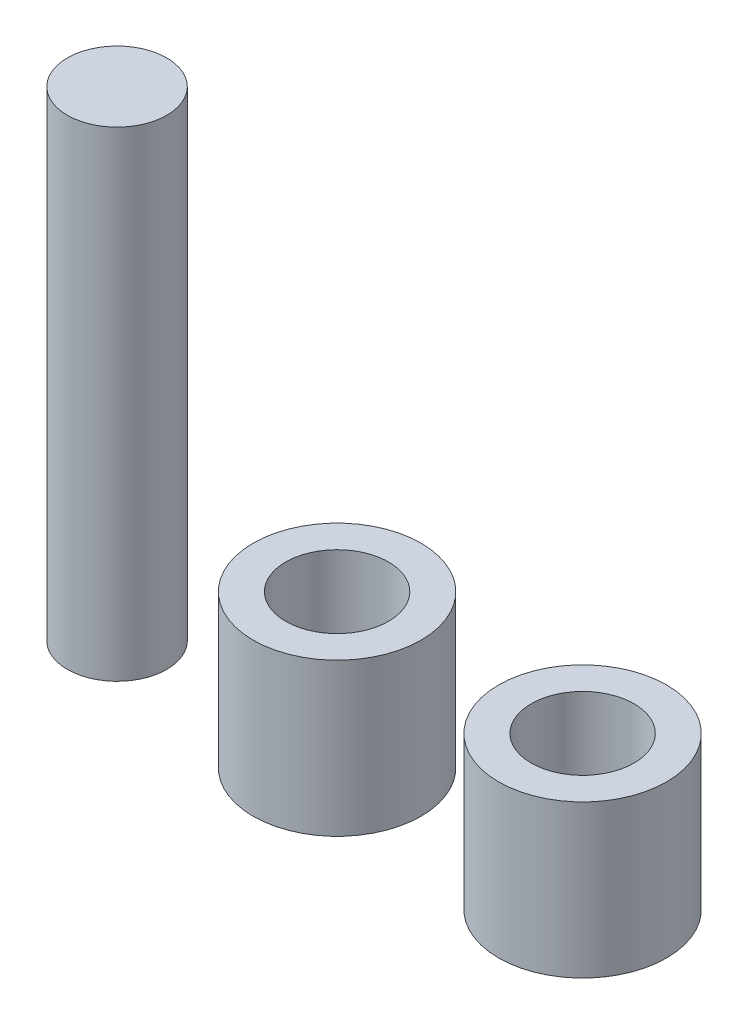
SolidWorks part; units mm, degrees
ref_plane "Front Plane" through (0, 0, 0) normal (0, 0, 1) x (1, 0, 0)
ref_plane "Top Plane" through (0, 0, 0) normal (0, 1, 0) x (1, 0, 0)
ref_plane "Right Plane" through (0, 0, 0) normal (1, 0, 0) x (0, 0, -1)
sketch "Sketch1" plane through (0, 0, 0) normal (0, 1, 0) x (1, 0, 0)
  line L0 (-3.5419, 0) -> (3.4353, 0) construction
  circle A0 centre (0, 0) radius 1.45
  dimension "D1" = 2.9
extrude "Boss-Extrude1" add sketch "Sketch1" along normal blind 14
sketch "Sketch2" plane through (0, 0, 0) normal (0, 1, 0) x (1, 0, 0)
  line L0 (-2.9584, 0) -> (3.1211, 0) construction
  line L1 (3.1211, 0) -> (7.9843, 0) construction
  circle A0 centre (6.4192, 0) radius 2.45
  dimension "D1" = 4.9
extrude "Boss-Extrude2" add sketch "Sketch2" along normal blind 4.45 contours A0
sketch "Sketch3" plane through (0, 4.45, 0) normal (0, 1, 0) x (1, 0, 0)
  line L0 (11.1987, 0) -> (1.6396, 0) construction
  line L1 (6.4192, 0) -> (6.4192, 2.8082) construction
  circle A0 centre (6.4192, 0) radius 1.5
  point P3 (0, 0)
  point P8 (6.0068, 0)
  point P9 (0, 0)
  point P10 (0, 0)
  dimension "D1" = 3
extrude "Cut-Extrude1" cut sketch "Sketch3" against normal through all
ref_plane "Plane1" through (10, 0, 0) normal (1, 0, 0) x (0, 0, -1)
mirror "Mirror23" about plane through (10, 0, 0) normal (1, 0, 0) of bodies 103
